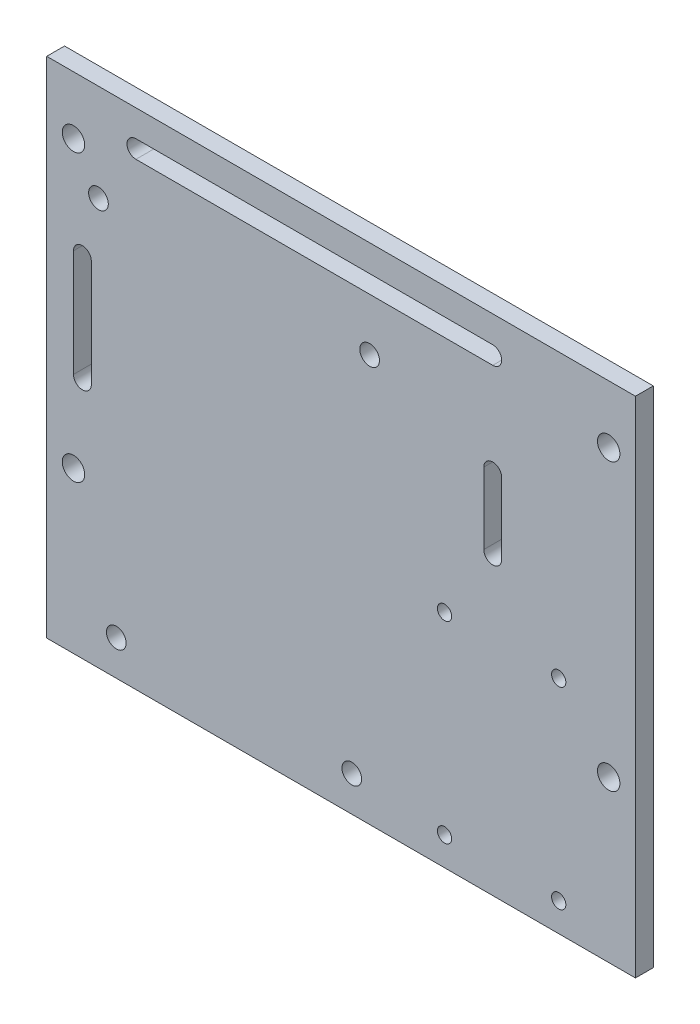
SolidWorks part; units mm, degrees
ref_plane "Front Plane" through (0, 0, 0) normal (0, 0, 1) x (1, 0, 0)
ref_plane "Top Plane" through (0, 0, 0) normal (0, 1, 0) x (1, 0, 0)
ref_plane "Right Plane" through (0, 0, 0) normal (1, 0, 0) x (0, 0, -1)
sketch "Sketch1" plane through (0, 0, 0) normal (0, 0, 1) x (1, 0, 0)
  line L1 (-52.3875, 57.15) -> (52.3875, 57.15)
  line L2 (-52.3875, 57.15) -> (-52.3875, -57.15)
  line L3 (-52.3875, -57.15) -> (52.3875, -57.15)
  line L4 (52.3875, 57.15) -> (52.3875, -57.15)
  line L5 (-52.3875, 57.15) -> (52.3875, -57.15) construction
  line L6 (-52.3875, -57.15) -> (52.3875, 57.15) construction
  point P0 (0, 0)
  dimension "D1" = 114.3
  dimension "D2" = 104.775
extrude "Boss-Extrude1" add sketch "Sketch1" along normal blind 3.175
sketch "Sketch2" plane through (0, 0, 3.175) normal (0, 0, 1) x (1, 0, 0)
  line L0 (-43.18, 15.24) -> (5.08, 15.24) construction
  line L1 (-40.005, -50.8762) -> (1.905, -50.8762) construction
  line L2 (-19.05, 15.24) -> (-19.05, -50.8762) construction
  circle A0 centre (-43.18, 15.24) radius 1.7526
  circle A1 centre (5.08, 15.24) radius 1.7526
  circle A2 centre (-40.005, -50.8762) radius 1.7526
  circle A3 centre (1.905, -50.8762) radius 1.7526
  dimension "D1" = 3.5052
  dimension "D2" = 48.26
  dimension "D3" = 41.91
  dimension "D4" = 66.1162
  dimension "D5" = 15.24
  dimension "D6" = 19.05
extrude "Cut-Extrude1" cut sketch "Sketch2" against normal through all
sketch "Sketch3" plane through (0, 0, 3.175) normal (0, 0, 1) x (1, 0, 0)
  line L1 (47.625, -28.575) -> (-47.625, -28.575) construction
  line L2 (47.625, -28.575) -> (47.625, 22.225) construction
  line L3 (47.625, 22.225) -> (-47.625, 22.225) construction
  line L4 (-47.625, -28.575) -> (-47.625, 22.225) construction
  line L5 (47.625, -28.575) -> (-47.625, 22.225) construction
  line L6 (47.625, 22.225) -> (-47.625, -28.575) construction
  circle A0 centre (-47.625, 22.225) radius 2
  circle A1 centre (47.625, 22.225) radius 2
  circle A2 centre (47.625, -28.575) radius 2
  circle A3 centre (-47.625, -28.575) radius 2
  point P0 (0, -3.175)
  dimension "D1" = 4
  dimension "D2" = 95.25
  dimension "D3" = 50.8
  dimension "D4" = 47.625
  dimension "D5" = 25.4
  dimension "D6" = 3.175
extrude "Cut-Extrude2" cut sketch "Sketch3" against normal through all
sketch "Sketch4" plane through (0, 0, 3.175) normal (0, 0, 1) x (1, 0, 0)
  line L1 (18.415, -17.78) -> (38.735, -17.78) construction
  line L2 (18.415, -17.78) -> (18.415, -52.07) construction
  line L3 (18.415, -52.07) -> (38.735, -52.07) construction
  line L4 (38.735, -17.78) -> (38.735, -52.07) construction
  line L5 (18.415, -17.78) -> (38.735, -52.07) construction
  line L6 (18.415, -52.07) -> (38.735, -17.78) construction
  circle A0 centre (18.415, -17.78) radius 1.27
  circle A1 centre (38.735, -17.78) radius 1.27
  circle A2 centre (38.735, -52.07) radius 1.27
  circle A3 centre (18.415, -52.07) radius 1.27
  point P0 (28.575, -34.925)
  dimension "D3" = 2.54
  dimension "D1" = 34.29
  dimension "D2" = 20.32
  dimension "D4" = 28.575
  dimension "D5" = 34.925
extrude "Cut-Extrude3" cut sketch "Sketch4" against normal through all
sketch "Sketch5" plane through (0, 0, 3.175) normal (0, 0, 1) x (1, 0, 0)
  line L0 (52.3875, 57.15) -> (-52.3875, 57.15) construction
  line L1 (-52.3875, 81.7811) -> (52.3875, 81.7811)
  line L2 (-52.3875, 81.7811) -> (-52.3875, 32.5189)
  line L3 (-52.3875, 32.5189) -> (52.3875, 32.5189)
  line L4 (52.3875, 81.7811) -> (52.3875, 32.5189)
  line L5 (-52.3875, 81.7811) -> (52.3875, 32.5189) construction
  line L6 (-52.3875, 32.5189) -> (52.3875, 81.7811) construction
  line L7 (52.3875, -57.15) -> (52.3875, 57.15) construction
  point P0 (0, 57.15)
extrude "Cut-Extrude4" cut sketch "Sketch5" against normal blind 15
sketch "Sketch7" plane through (0, 0, 3.175) normal (0, 0, 1) x (1, 0, 0)
  line L0 (-46.0375, 4.9243) -> (-46.0375, -14.1257) construction
  line L1 (-44.45, 4.9243) -> (-44.45, -14.1257)
  line L2 (-47.625, 4.9243) -> (-47.625, -14.1257)
  line L3 (-52.3875, 32.5189) -> (-52.3875, -57.15) construction
  line L4 (-36.5125, 26.1689) -> (26.9875, 26.1689) construction
  line L5 (-36.5125, 27.7564) -> (26.9875, 27.7564)
  line L6 (-36.5125, 24.5814) -> (26.9875, 24.5814)
  line L7 (-52.3875, 32.5189) -> (52.3875, 32.5189) construction
  line L8 (26.9875, 8.0993) -> (26.9875, -4.6007) construction
  line L9 (28.575, 8.0993) -> (28.575, -4.6007)
  line L10 (25.4, 8.0993) -> (25.4, -4.6007)
  line L11 (52.3875, -57.15) -> (52.3875, 32.5189) construction
  arc A0 (-44.45, 4.9243) -> (-47.625, 4.9243) centre (-46.0375, 4.9243) ccw
  arc A1 (-47.625, -14.1257) -> (-44.45, -14.1257) centre (-46.0375, -14.1257) ccw
  arc A2 (-36.5125, 27.7564) -> (-36.5125, 24.5814) centre (-36.5125, 26.1689) ccw
  arc A3 (26.9875, 24.5814) -> (26.9875, 27.7564) centre (26.9875, 26.1689) ccw
  arc A4 (28.575, 8.0993) -> (25.4, 8.0993) centre (26.9875, 8.0993) ccw
  arc A5 (25.4, -4.6007) -> (28.575, -4.6007) centre (26.9875, -4.6007) ccw
  point P2 (-46.0375, -4.6007)
  point P7 (-4.7625, 26.1689)
  point P16 (26.9875, 1.7493)
  point P25 (-46.0375, -4.6007)
  point P28 (0, 0)
  dimension "D7" = 1.5875
  dimension "D1" = 3.175
  dimension "D2" = 19.05
  dimension "D3" = 6.35
  dimension "D4" = 6.35
  dimension "D5" = 3.175
  dimension "D6" = 63.5
  dimension "D8" = 12.7
  dimension "D9" = 25.4
extrude "Cut-Extrude5" cut sketch "Sketch7" against normal through all
